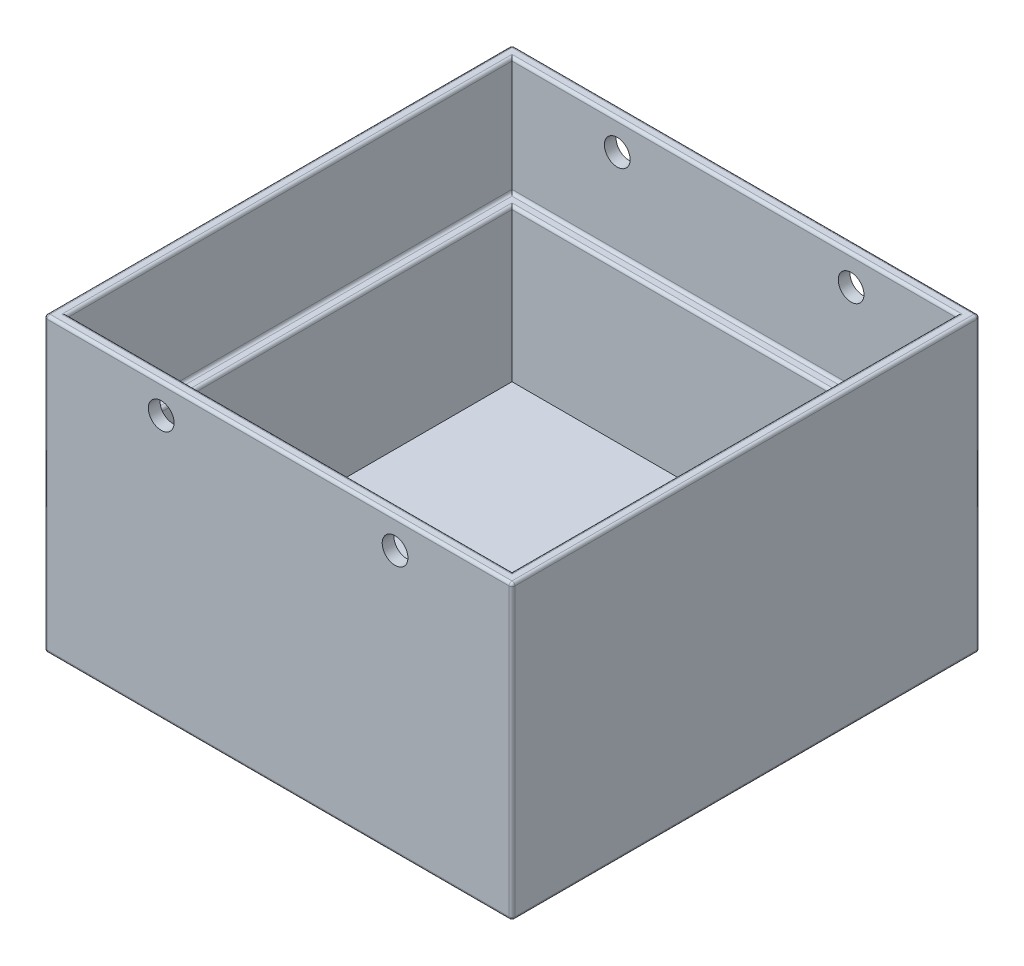
SolidWorks part; units mm, degrees
ref_plane "Front Plane" through (0, 0, 0) normal (0, 0, 1) x (1, 0, 0)
ref_plane "Top Plane" through (0, 0, 0) normal (0, 1, 0) x (1, 0, 0)
ref_plane "Right Plane" through (0, 0, 0) normal (1, 0, 0) x (0, 0, -1)
sketch "Sketch1" plane through (0, 0, 0) normal (0, 0, 1) x (1, 0, 0)
  line L1 (0, 0) -> (80, 0)
  line L2 (0, 0) -> (0, 50)
  line L3 (0, 50) -> (80, 50)
  line L4 (80, 0) -> (80, 50)
  dimension "D1" = 50
  dimension "D2" = 80
extrude "Boss-Extrude1" add sketch "Sketch1" along normal blind 80
shell "Shell1" thickness 4
sketch "Sketch2" plane through (0, 50, 0) normal (0, 1, 0) x (1, 0, 0)
  line L0 (2, -2) -> (2, -78)
  line L1 (0, 0) -> (80, 0)
  line L2 (0, 0) -> (0, -80)
  line L3 (0, -80) -> (80, -80)
  line L4 (80, 0) -> (80, -80)
  line L5 (2, -78) -> (78, -78)
  line L6 (78, -2) -> (78, -78)
  line L7 (2, -2) -> (78, -2)
  line L9 (4, -4) -> (76, -4)
  line L10 (4, -4) -> (4, -76)
  line L11 (4, -76) -> (76, -76)
  line L12 (76, -4) -> (76, -76)
  line M6 (4, -4) -> (76, -4)
  line M7 (76, -4) -> (76, -76)
  line M8 (76, -76) -> (4, -76)
  line M9 (4, -76) -> (4, -4)
  dimension "D1" = 2
extrude "Cut-Extrude1" cut sketch "Sketch2" against normal blind 20 contours L7 L0 L5 L6 M9 M6 M7 M8
sketch "Sketch3" plane through (0, 0, 80) normal (0, 0, 1) x (1, 0, 0)
  line L0 (40, 50) -> (40, 45) construction
  line L1 (80, 50) -> (0, 50) construction
  line L2 (40, 45) -> (0, 45) construction
  line L3 (0, 50) -> (0, 0) construction
  line L4 (40, 45) -> (80, 45) construction
  line L5 (80, 0) -> (80, 50) construction
  circle A0 centre (20, 45) radius 2.2
  circle A1 centre (60, 45) radius 2.2
  dimension "D1" = 4.4
  dimension "D2" = 5
extrude "Cut-Extrude2" cut sketch "Sketch3" against normal through all
fillet "Fillet1" radius 0.5 24 edges at (0, 0, 40) (40, 0, 80) (80, 0, 40) (40, 0, 0) (2, 50, 40) (40, 50, 78) (78, 50, 40) (40, 50, 2) (80, 50, 40) (40, 50, 80) (0, 50, 40) (40, 50, 0) (40, 30, 76) (76, 30, 40) (40, 30, 4) (4, 30, 40) (78, 30, 40) (40, 30, 78) (2, 30, 40) (40, 30, 2) (80, 25, 80) (80, 25, 0) (0, 25, 0) (0, 25, 80)
